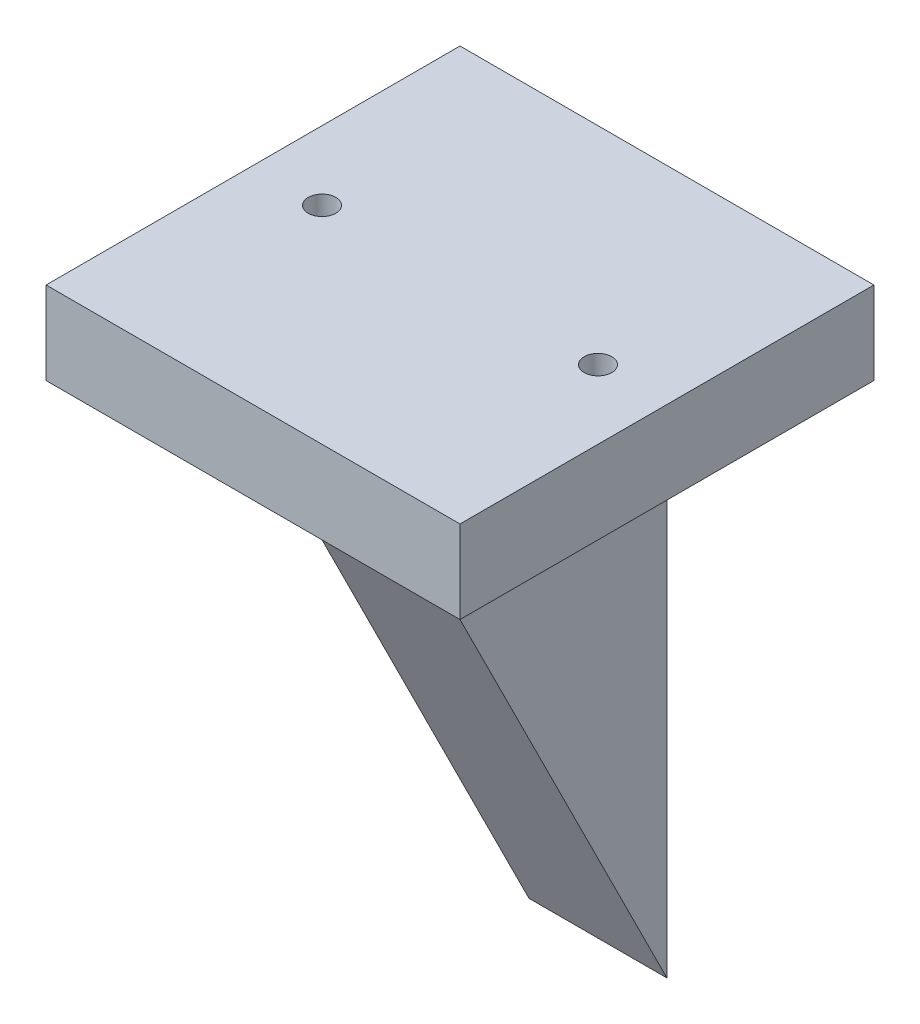
SolidWorks part; units mm, degrees
material "Кованая нержавеющая сталь"
ref_plane "Front" through (0, 0, 0) normal (0, 0, 1) x (1, 0, 0)
ref_plane "Top" through (0, 0, 0) normal (0, 1, 0) x (1, 0, 0)
ref_plane "Right" through (0, 0, 0) normal (1, 0, 0) x (0, 0, -1)
sketch "Эскиз1" plane through (0, 0, 0) normal (1, 0, 0) x (0, 0, -1)
  line L0 (-10, 20) -> (0, 0)
  line L2 (0, 0) -> (0, 20)
  line L3 (0, 20) -> (-10, 20)
  dimension "D1" = 10
  dimension "D2" = 20
extrude "Бобышка-Вытянуть1" add sketch "Эскиз1" along normal blind 5
sketch "Эскиз2" plane through (0, 20, 0) normal (0, 1, 0) x (1, 0, 0)
  line L0 (0, 0) -> (5, -10) construction
  line L1 (7.5, -5) -> (-2.5, -5) construction
  line L4 (-5, -12.5) -> (10, -12.5)
  line L5 (-5, -12.5) -> (-5, 2.5)
  line L6 (-5, 2.5) -> (10, 2.5)
  line L7 (10, -12.5) -> (10, 2.5)
  line L8 (-5, -12.5) -> (10, 2.5) construction
  line L9 (-5, 2.5) -> (10, -12.5) construction
  circle A0 centre (-2.5, -5) radius 0.5
  circle A1 centre (7.5, -5) radius 0.5
  point P7 (2.5, -5)
  point P9 (2.5, -5)
  dimension "D4" = 1
  dimension "D5" = 1
  dimension "D1" = 15
  dimension "D2" = 15
  dimension "D3" = 10
extrude "Бобышка-Вытянуть2" add sketch "Эскиз2" along normal blind 3
